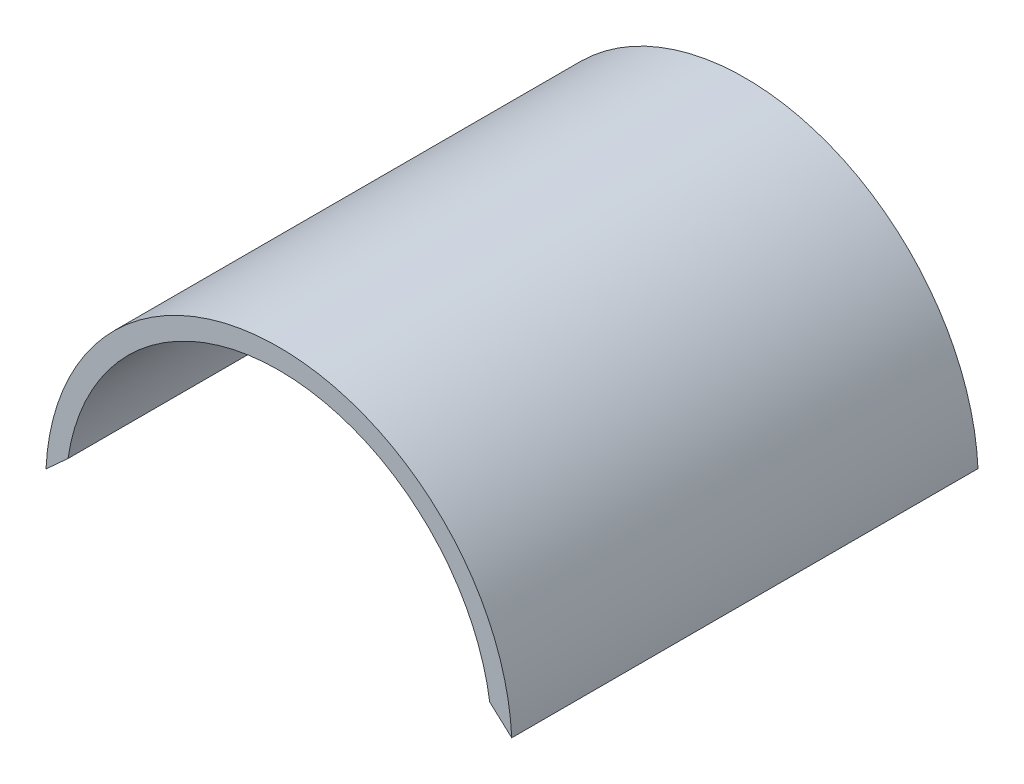
SolidWorks part; units mm, degrees
ref_plane "Front Plane" through (0, 0, 0) normal (0, 0, 1) x (1, 0, 0)
ref_plane "Top Plane" through (0, 0, 0) normal (0, 1, 0) x (1, 0, 0)
ref_plane "Right Plane" through (0, 0, 0) normal (1, 0, 0) x (0, 0, -1)
sketch "Sketch1" plane through (0, 0, 0) normal (0, 0, 1) x (1, 0, 0)
  line L0 (0, 0) -> (0, 44.45) construction
  line L1 (-40.2039, 5.9378) -> (40.2039, 5.9378) construction
  line L2 (-44.399, 2.1278) -> (44.399, 2.1278) construction
  line L3 (-40.2039, 5.9378) -> (-44.399, 2.1278)
  line L4 (40.2039, 5.9378) -> (44.399, 2.1278)
  arc A0 (44.399, 2.1278) -> (-44.399, 2.1278) centre (0, 0) ccw
  arc A1 (40.2039, 5.9378) -> (-40.2039, 5.9378) centre (0, 0) ccw
  dimension "D1" = 88.9
  dimension "D2" = 3.81
  dimension "D3" = 3.81
extrude "Boss-Extrude1" add sketch "Sketch1" along normal blind 88.9
sketch "Sketch2" plane through (-21.1272, 23.263, 0) normal (0.6723, -0.7403, 0) x (0.7403, 0.6723, 0)
  line L0 (-28.6033, 88.9) -> (-28.6033, -0.0227) construction
  line L1 (-31.4368, 88.9) -> (-25.7698, 88.9) construction
  line L2 (-31.4368, 44.45) -> (-25.7698, 44.45) construction
  line L3 (-31.4368, 88.9) -> (-31.4368, 0) construction
  line L4 (-25.7698, 88.9) -> (-25.7698, 0) construction
  circle A0 centre (-28.6033, 63.4887) radius 4
  point P12 (-28.6033, 44.4387)
  dimension "D1" = 8
  dimension "D2" = 19.05
